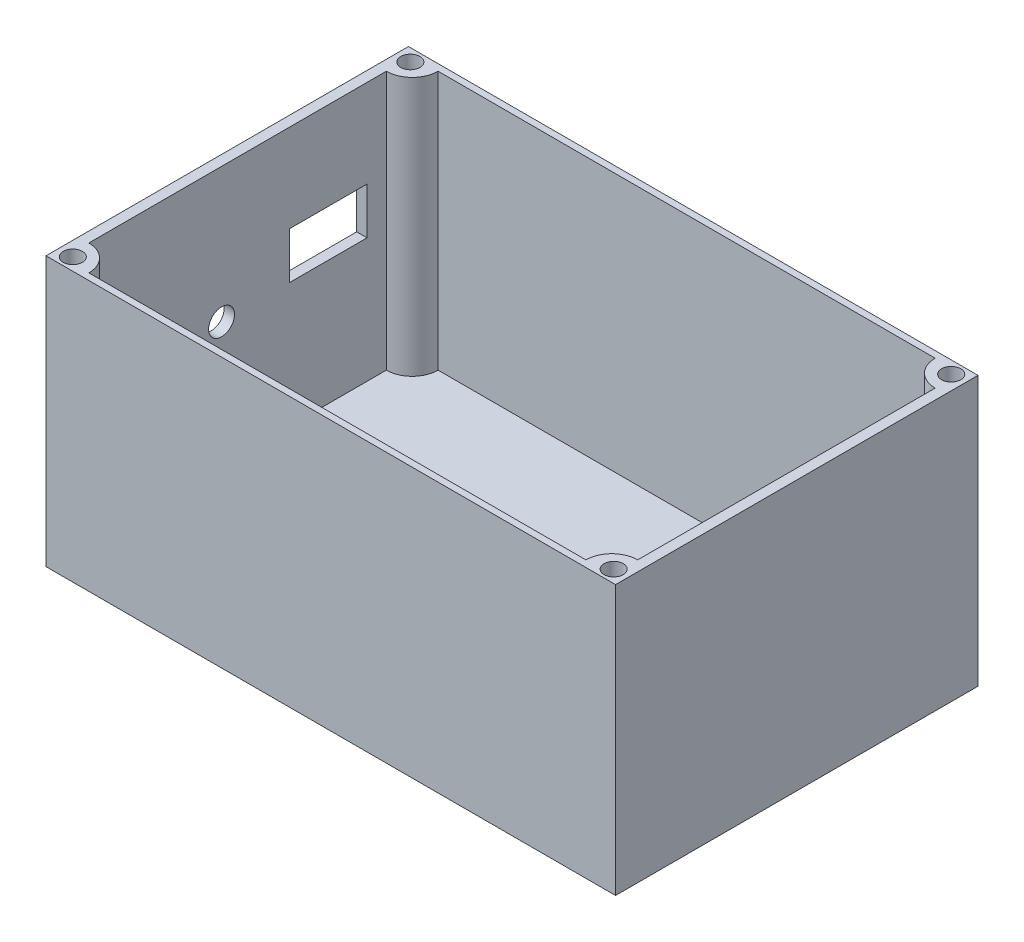
SolidWorks part; units mm, degrees
ref_plane "Ön Düzlem" through (0, 0, 0) normal (0, 0, 1) x (1, 0, 0)
ref_plane "Üst Düzlem" through (0, 0, 0) normal (0, 1, 0) x (1, 0, 0)
ref_plane "Sağ Düzlem" through (0, 0, 0) normal (1, 0, 0) x (0, 0, -1)
sketch "Çizim1" plane through (0, 0, 0) normal (0, 1, 0) x (1, 0, 0)
  line L1 (-55, -35) -> (55, -35)
  line L2 (-55, -35) -> (-55, 35)
  line L3 (-55, 35) -> (55, 35)
  line L4 (55, -35) -> (55, 35)
  line L5 (-55, -35) -> (55, 35) construction
  line L6 (-55, 35) -> (55, -35) construction
  point P0 (0, 0)
extrude "Yükseklik-Ekstrüzyon1" add sketch "Çizim1" along normal blind 2
sketch "Çizim2" plane through (0, 2, 0) normal (0, 1, 0) x (1, 0, 0)
  line L0 (-48.7817, 31.0429) -> (48.7817, -31.0429) construction
  line L1 (-55, -35) -> (55, -35)
  line L2 (-55, -35) -> (-55, 35)
  line L3 (-55, 35) -> (55, 35)
  line L4 (55, -35) -> (55, 35)
  line L6 (-55, 35) -> (-53, 33.7273) construction
  line L7 (-48, -33.7273) -> (48, -33.7273)
  line L8 (-53, -28.7273) -> (-53, 28.7273)
  line L9 (-48, 33.7273) -> (48, 33.7273)
  line L10 (53, -28.7273) -> (53, 28.7273)
  line L11 (-48.7817, -31.0429) -> (48.7817, 31.0429) construction
  line L12 (-48.7817, 31.0429) -> (48.7817, -31.0429) construction
  line L13 (-48.7817, -31.0429) -> (48.7817, 31.0429) construction
  arc A0 (-53, 28.7273) -> (-48, 33.7273) centre (-53, 33.7273) ccw
  arc A1 (-48, -33.7273) -> (-53, -28.7273) centre (-53, -33.7273) ccw
  arc A2 (53, -28.7273) -> (48, -33.7273) centre (53, -33.7273) ccw
  arc A3 (48, 33.7273) -> (53, 28.7273) centre (53, 33.7273) ccw
  point P0 (0, 0)
  point P5 (0, 0)
  dimension "D1" = 2
  dimension "D2" = 1.2727
extrude "Yükseklik-Ekstrüzyon2" add sketch "Çizim2" along normal blind 50
sketch "Çizim3" plane through (-55, 0, 0) normal (-1, 0, 0) x (0, 0, 1)
  circle A0 centre (21.6886, 26) radius 5.5
extrude "Kes-Ekstrüzyon1" cut sketch "Çizim3" against normal blind 13
sketch "Çizim4" plane through (-55, 0, 0) normal (-1, 0, 0) x (0, 0, 1)
  line L3 (-25, 26) -> (-25, 35)
  line L4 (-25, 35) -> (-10, 35)
  line L5 (-10, 35) -> (-10, 26)
  line L6 (-10, 26) -> (-25, 26)
  circle A1 centre (3.0943, 26) radius 2.5
extrude "Kes-Ekstrüzyon2" cut sketch "Çizim4" against normal blind 13
sketch "Çizim5" plane through (0, 52, 0) normal (0, 1, 0) x (1, 0, 0)
  circle A2 centre (-52.2322, 32.5959) radius 1.85
  circle A6 centre (52.2322, 32.5959) radius 1.85
  circle A7 centre (52.2322, -32.5959) radius 1.85
  circle A8 centre (-52.2322, -32.5959) radius 1.85
  point P13 (0, 0)
  dimension "D1" = 3.7
extrude "Kes-Ekstrüzyon3" cut sketch "Çizim5" against normal blind 67
